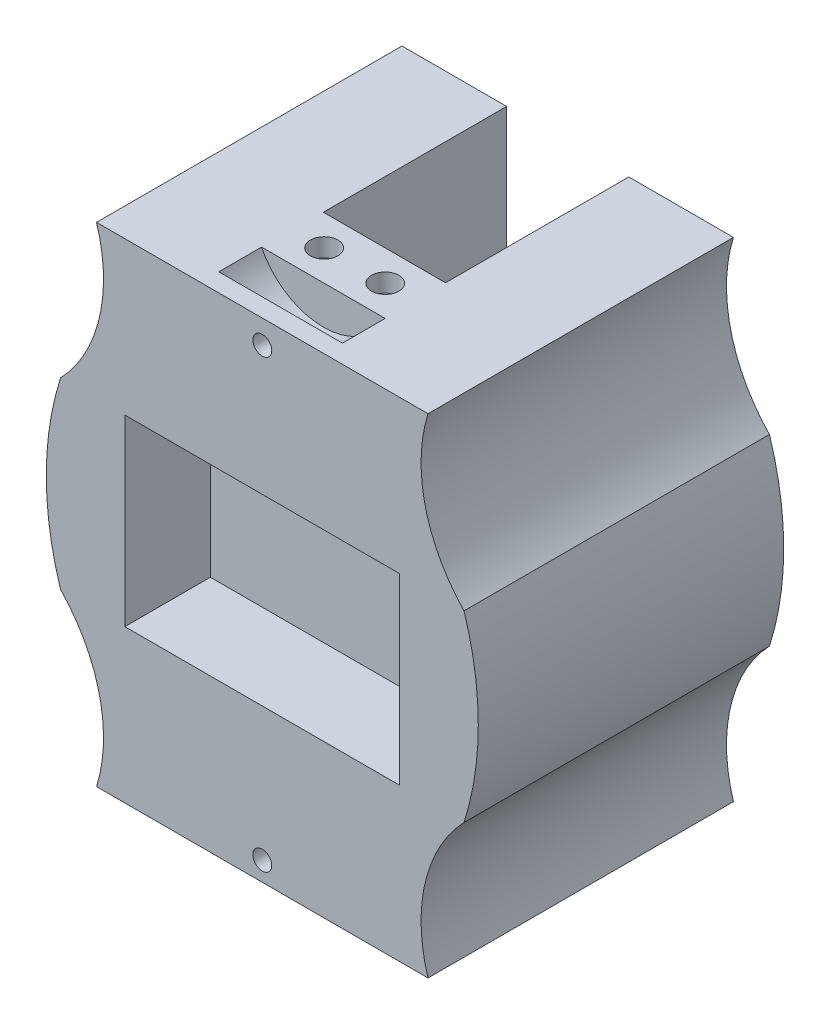
SolidWorks part; units mm, degrees
ref_plane "前视基准面" through (0, 0, 0) normal (0, 0, 1) x (1, 0, 0)
ref_plane "上视基准面" through (0, 0, 0) normal (0, 1, 0) x (1, 0, 0)
ref_plane "右视基准面" through (0, 0, 0) normal (1, 0, 0) x (0, 0, -1)
sketch "草图1" plane through (0, 0, 0) normal (0, 0, 1) x (1, 0, 0)
  line L0 (-50, -40) -> (-32.5, -40)
  line L1 (-50, 40) -> (50, 40)
  line L2 (-50, 40) -> (-50, -40)
  line L3 (-50, -40) -> (50, -40)
  line L4 (50, 40) -> (50, -40)
  line L5 (-50, 40) -> (50, -40) construction
  line L6 (-50, -40) -> (50, 40) construction
  line L7 (-32.5, -40) -> (32.5, -40)
  line L8 (-32.5, -40) -> (-32.5, 40)
  line L9 (-32.5, 40) -> (32.5, 40)
  line L10 (32.5, -40) -> (32.5, 40)
  line L11 (-32.5, -40) -> (32.5, 40) construction
  line L12 (-32.5, 40) -> (32.5, -40) construction
  line L13 (-50, 15) -> (50, 15)
  line L14 (-50, 15) -> (-50, -15)
  line L15 (-50, -15) -> (50, -15)
  line L16 (50, 15) -> (50, -15)
  line L17 (-50, 15) -> (50, -15) construction
  line L18 (-50, -15) -> (50, 15) construction
  line L19 (0, 0) -> (0, -24.7451) construction
  line L20 (0, -24.7451) -> (0, 0) construction
  line L21 (0, 0) -> (19.4056, 0) construction
  arc A0 (-50, -15) -> (-41.25, -40) centre (-58.125, -31.875) cw
  arc A1 (50, -15) -> (41.25, -40) centre (58.125, -31.875) ccw
  arc A2 (50, 15) -> (41.25, 40) centre (58.125, 31.875) cw
  arc A3 (-50, 15) -> (-41.25, 40) centre (-58.125, 31.875) ccw
  point P0 (0, 0)
  point P6 (0, 0)
  point P11 (0, 0)
  dimension "D1" = 100
  dimension "D2" = 80
  dimension "D3" = 65
  dimension "D4" = 30
  dimension "D5" = 0
extrude "凸台-拉伸1" add sketch "草图1" along normal blind 30 contours L8 L13 L10 L1 | A3 L13 L8 L1 | L13 A2 L1 L10 | L10 L15 L4 L13 | L8 L15 L10 L13 | L2 L15 L8 L13 | L15 A0 L3 L8 | L15 L8 L3 L10 | A1 L15 L10 L3
sketch "草图2" plane through (0, 0, 30) normal (0, 0, 1) x (1, 0, 0)
  line L0 (-41.25, 40) -> (41.25, 40) construction
  line L5 (41.25, 40) -> (0, 40) construction
  line L6 (-41.25, 40) -> (-56.5468, 71.4803)
  line L11 (0, 0) -> (0, 40) construction
  line L12 (10.1194, 40) -> (41.25, 40)
  line L13 (-87.5, 15) -> (-12.5, 15)
  line L14 (-41.25, 40) -> (-56.5468, 71.4803)
  line L16 (-56.5468, 71.4803) -> (-31.3626, 83.7177)
  line L19 (-87.5, 15) -> (-87.5, -15)
  line L20 (-10.1194, 40) -> (-41.25, 40)
  line L21 (56.5468, 71.4803) -> (31.3626, 83.7177)
  line L22 (41.25, 40) -> (56.5468, 71.4803)
  line L23 (-50, 15) -> (-50, -15) construction
  line L24 (-50, -15) -> (-50, 0) construction
  line L25 (-50, 0) -> (50, 0) construction
  line L26 (50, 15) -> (50, -15) construction
  line L27 (-10.1194, -40) -> (-41.25, -40)
  line L28 (-41.25, -40) -> (-56.5468, -71.4803)
  line L29 (-56.5468, -71.4803) -> (-31.3626, -83.7177)
  line L30 (56.5468, -71.4803) -> (31.3626, -83.7177)
  line L31 (41.25, -40) -> (56.5468, -71.4803)
  line L32 (10.1194, -40) -> (41.25, -40)
  line L33 (-87.5, -15) -> (-12.5, -15)
  line L34 (-12.5, 15) -> (-12.5, -15)
  line L35 (-87.5, 15) -> (-12.5, -15) construction
  line L36 (-87.5, -15) -> (-12.5, 15) construction
  line L37 (87.5, -15) -> (12.5, -15)
  line L38 (12.5, 15) -> (12.5, -15)
  line L39 (87.5, 15) -> (12.5, 15)
  line L40 (87.5, 15) -> (87.5, -15)
  arc A0 (-31.3626, 83.7177) -> (-10.1194, 40) centre (45.9871, 94.2833) ccw
  arc A1 (31.3626, 83.7177) -> (10.1194, 40) centre (-45.9871, 94.2833) cw
  arc A2 (-31.3626, -83.7177) -> (-10.1194, -40) centre (45.9871, -94.2833) cw
  arc A3 (31.3626, -83.7177) -> (10.1194, -40) centre (-45.9871, -94.2833) ccw
  line M6 (41.25, 40) -> (-41.25, 40)
  line M8 (-50, 15) -> (-50, -15)
  line M10 (-41.25, -40) -> (41.25, -40)
  line M12 (50, -15) -> (50, 15)
  dimension "D1" = 35
  dimension "D2" = 28
  dimension "D3" = 75
extrude "凸台-拉伸2" add sketch "草图2" against normal blind 10 contours L40 L39 L37 M12 | L21 A1 L22 M6 | A0 L16 L6 M6 | L19 L33 L13 M8 | L29 A2 L28 M10 | A3 L30 L31 M10
sketch "草图3" plane through (0, 0, 30) normal (0, 0, 1) x (1, 0, 0)
  line L0 (-10.1194, 40) -> (10.1194, 40)
  line L1 (-10.1194, 40) -> (10.1194, 40) construction
  line L2 (10.1194, 40) -> (30.1194, 40)
  line L3 (50, 15) -> (35, 15)
  line L4 (0, 0) -> (0, -59.6599) construction
  line L5 (0, -59.6599) -> (0, 0) construction
  line L6 (-101.1534, 0) -> (101.1534, 0) construction
  line L7 (-10.1194, 40) -> (-30.1194, 40)
  line L8 (-50, 15) -> (-35, 15)
  line L9 (10.1194, -40) -> (30.1194, -40)
  line L10 (-10.1194, -40) -> (10.1194, -40)
  line L11 (-10.1194, -40) -> (-30.1194, -40)
  arc A0 (10.1194, 40) -> (31.3626, 83.7177) centre (-45.9871, 94.2833) ccw construction
  arc A1 (30.1194, 40) -> (35, 15) centre (64.7114, 33.7768) ccw
  arc A2 (-30.1194, 40) -> (-35, 15) centre (-64.7114, 33.7768) cw
  arc A3 (30.1194, -40) -> (35, -15) centre (64.7114, -33.7768) cw
  arc A4 (-30.1194, -40) -> (-35, -15) centre (-64.7114, -33.7768) ccw
  arc A5 (-35, 15) -> (-35, -15) centre (-3.9777, 0) ccw
  arc A6 (35, 15) -> (35, -15) centre (3.9777, 0) cw
  arc A7 (-10.1194, 40) -> (10.1194, 40) centre (0, 44.9919) ccw
  arc A8 (-10.1194, -40) -> (10.1194, -40) centre (0, -44.9919) cw
  line M7 (10.1194, 40) -> (-10.1194, 40)
  arc M8 (-10.1194, 40) -> (-31.3626, 83.7177) centre (45.9871, 94.2833) cw
  line M9 (-31.3626, 83.7177) -> (-56.5468, 71.4803)
  line M10 (-56.5468, 71.4803) -> (-41.25, 40)
  arc M11 (-41.25, 40) -> (-50, 15) centre (-58.125, 31.875) cw
  line M12 (-50, 15) -> (-87.5, 15)
  line M13 (-87.5, 15) -> (-87.5, -15)
  line M14 (-87.5, -15) -> (-50, -15)
  arc M15 (-50, -15) -> (-41.25, -40) centre (-58.125, -31.875) cw
  line M16 (-41.25, -40) -> (-56.5468, -71.4803)
  line M17 (-56.5468, -71.4803) -> (-31.3626, -83.7177)
  arc M18 (-31.3626, -83.7177) -> (-10.1194, -40) centre (45.9871, -94.2833) cw
  line M19 (-10.1194, -40) -> (10.1194, -40)
  arc M20 (10.1194, -40) -> (31.3626, -83.7177) centre (-45.9871, -94.2833) cw
  line M21 (31.3626, -83.7177) -> (56.5468, -71.4803)
  line M22 (56.5468, -71.4803) -> (41.25, -40)
  arc M23 (41.25, -40) -> (50, -15) centre (58.125, -31.875) cw
  line M24 (50, -15) -> (87.5, -15)
  line M25 (87.5, -15) -> (87.5, 15)
  line M26 (87.5, 15) -> (50, 15)
  arc M27 (50, 15) -> (41.25, 40) centre (58.125, 31.875) cw
  line M28 (41.25, 40) -> (56.5468, 71.4803)
  line M29 (56.5468, 71.4803) -> (31.3626, 83.7177)
  arc M30 (31.3626, 83.7177) -> (10.1194, 40) centre (-45.9871, 94.2833) cw
  dimension "D1" = 20
  dimension "D2" = 20.2388
  dimension "D3" = 15
extrude "切除-拉伸2" cut sketch "草图3" against normal blind 10 contours A2 L7 L8 M8 M9 M10 M11 | L2 A1 L3 M27 M28 M29 M30 | L3 A6 A3 L9 M20 M21 M22 M23 M24 M25 M26 | A5 L8 L11 A4 M12 M13 M14 M15 M16 M17 M18 | A7 M7 | A8 M19
sketch "草图4" plane through (0, 0, 30) normal (0, 0, 1) x (1, 0, 0)
  line L1 (-22.5, 15) -> (22.5, 15)
  line L2 (-22.5, 15) -> (-22.5, -15)
  line L3 (-22.5, -15) -> (22.5, -15)
  line L4 (22.5, 15) -> (22.5, -15)
  line L5 (-22.5, 15) -> (22.5, -15) construction
  line L6 (-22.5, -15) -> (22.5, 15) construction
  point P0 (0, 0)
  dimension "D1" = 30
  dimension "D2" = 45
extrude "切除-拉伸3" cut sketch "草图4" against normal blind 6 contours L2 L1 L4 L3
sketch "草图5" plane through (0, 0, 30) normal (0, 0, 1) x (1, 0, 0)
  line L0 (-35, 15) -> (-22.5, 15)
  line L1 (-22.5, 15) -> (-22.5, -15) construction
  line L2 (-22.5, 15) -> (22.5, 15) construction
  line L3 (-35, -15) -> (-22.5, -15)
  line L4 (0, 0) -> (-12.8145, 0)
  line L5 (-12.8145, 0) -> (0, 0)
  line L6 (0, -22.7736) -> (0, 22.7736)
  line L7 (-27.1337, 40) -> (-30.1194, 40)
  arc A0 (-30.1194, 40) -> (-35, 15) centre (-64.7114, 33.7768) cw
  arc A1 (-27.1337, 40) -> (-33.0272, 15) centre (-51.2597, 32.4928) cw
  arc A2 (-35, 15) -> (-35, -15) centre (-3.9777, 0) ccw
  arc A3 (-33.0272, 15) -> (-33.0272, -15) centre (14.0025, 0) ccw
  arc A4 (-27.1337, -40) -> (-33.0272, -15) centre (-51.2597, -32.4928) ccw
  arc A5 (27.1337, -40) -> (33.0272, -15) centre (51.2597, -32.4928) cw
  arc A6 (33.0272, 15) -> (33.0272, -15) centre (-14.0025, 0) cw
  arc A7 (27.1337, 40) -> (33.0272, 15) centre (51.2597, 32.4928) ccw
extrude "切除-拉伸13" cut sketch "草图5" against normal blind 16
sketch "草图6" plane through (0, 0, 30) normal (0, 0, 1) x (1, 0, 0)
  line L0 (-10.1194, 40) -> (10.1194, 40)
  line L1 (-10.1194, -40) -> (10.1194, -40)
  arc A0 (-10.1194, -40) -> (10.1194, -40) centre (0, -44.9919) cw
  arc A1 (-10.1194, 40) -> (10.1194, 40) centre (0, 44.9919) ccw
extrude "凸台-拉伸3" add sketch "草图6" against normal blind 3
sketch "草图7" plane through (0, 0, 27) normal (0, 0, -1) x (-1, 0, 0)
  line L0 (0, -40) -> (0, -33.7082)
  line L1 (10.1194, -40) -> (-10.1194, -40) construction
  line L2 (0, -33.7082) -> (0, -36.8541)
  arc A0 (10.1194, -40) -> (-10.1194, -40) centre (0, -44.9919) ccw construction
  circle A1 centre (0, -36.8541) radius 1.55
  dimension "D1" = 3.1
extrude "切除-拉伸14" cut sketch "草图7" against normal blind 3 contours L0 A1 | L0 A1
sketch "草图8" plane through (0, 0, 27) normal (0, 0, -1) x (-1, 0, 0)
  line L0 (0, -36.8541) -> (0, 36.1459)
  circle A1 centre (0, 36.1459) radius 1.55
  dimension "D1" = 3.1
  dimension "D2" = 73
extrude "切除-拉伸16" cut sketch "草图8" against normal blind 6.1008
sketch "草图10" plane through (0, 0, 30) normal (0, 0, 1) x (1, 0, 0)
  line L0 (-27.1337, 40) -> (27.1337, 40)
  line L1 (27.1337, -40) -> (-27.1337, -40)
  line L2 (-155.6464, 80.8632) -> (70.8313, 55.9354)
  line L3 (70.8313, 55.9354) -> (148.6545, 0)
  line L4 (148.6545, 0) -> (148.6545, -24.3198)
  line L5 (1.824, -88.1591) -> (-119.4708, -24.3198)
  line L6 (-119.4708, -24.3198) -> (-155.6464, 80.8632)
  line L7 (1.824, -88.1591) -> (148.6545, -24.3198)
  arc A0 (27.1337, 40) -> (33.0272, 15) centre (51.2597, 32.4928) ccw
  arc A1 (33.0272, 15) -> (33.0272, -15) centre (-14.0025, 0) cw
  arc A2 (33.0272, -15) -> (27.1337, -40) centre (51.2597, -32.4928) ccw
  arc A3 (-27.1337, 40) -> (-33.0272, 15) centre (-51.2597, 32.4928) cw
  arc A4 (-33.0272, 15) -> (-33.0272, -15) centre (14.0025, 0) ccw
  arc A5 (-33.0272, -15) -> (-27.1337, -40) centre (-51.2597, -32.4928) cw
extrude "切除-拉伸17" cut sketch "草图10" against normal blind 70
sketch "草图11" plane through (0, 0, 0) normal (0, 0, -1) x (-1, 0, 0)
  line L0 (-27.1337, 40) -> (27.1337, 40)
  line L1 (-27.1337, -40) -> (27.1337, -40)
  arc A0 (27.1337, 40) -> (33.0272, 15) centre (51.2597, 32.4928) ccw
  arc A1 (33.0272, 15) -> (33.0272, -15) centre (-14.0025, 0) cw
  arc A2 (33.0272, -15) -> (27.1337, -40) centre (51.2597, -32.4928) ccw
  arc A3 (-27.1337, -40) -> (-33.0272, -15) centre (-51.2597, -32.4928) ccw
  arc A4 (-33.0272, -15) -> (-33.0272, 15) centre (14.0025, 0) cw
  arc A5 (-33.0272, 15) -> (-27.1337, 40) centre (-51.2597, 32.4928) ccw
extrude "凸台-拉伸4" add sketch "草图11" along normal blind 20
sketch "草图19" plane through (0, 40, 0) normal (0, 1, 0) x (1, 0, 0)
  line L0 (-27.1337, 20) -> (27.1337, 20) construction
  line L1 (-10, 50) -> (10, 50)
  line L2 (-10, 50) -> (-10, -10)
  line L3 (-10, -10) -> (10, -10)
  line L4 (10, 50) -> (10, -10)
  line L5 (-10, 50) -> (10, -10) construction
  line L6 (-10, -10) -> (10, 50) construction
  point P0 (0, 20)
  dimension "D1" = 20
  dimension "D2" = 60
extrude "切除-拉伸25" cut sketch "草图19" against normal blind 26.5
sketch "草图20" plane through (0, 0, -20) normal (0, 0, -1) x (-1, 0, 0)
  line L0 (-10, 13.5) -> (-10, 8.5)
  line L1 (-10, 8.5) -> (-4.875, 8.5)
  circle A0 centre (-4.875, 8.5) radius 2.25
  dimension "D3" = 4.5
  dimension "D1" = 5
  dimension "D2" = 5.125
sketch "草图21" plane through (0, 40, 0) normal (0, 1, 0) x (1, 0, 0)
  line L0 (-10, -10) -> (-10, -15)
  line L1 (-10, -15) -> (-4.875, -15)
  circle A0 centre (-4.875, -15) radius 2.25
  dimension "D3" = 4.5
  dimension "D1" = 5
  dimension "D2" = 5.125
extrude "切除-拉伸27" cut sketch "草图21" against normal blind 3
sketch "草图22" plane through (0, 40, 0) normal (0, 1, 0) x (1, 0, 0)
  line L0 (-4.875, -15) -> (5.125, -15)
  circle A0 centre (5.125, -15) radius 2.25
  dimension "D2" = 4.5
  dimension "D1" = 10
extrude "切除-拉伸28" cut sketch "草图22" against normal blind 3 contours A0
sketch "草图23" plane through (0, 0, -20) normal (0, 0, -1) x (-1, 0, 0)
  line L0 (-33.0272, 15) -> (-33.0272, -15)
  line L1 (-10, 40) -> (10, 40)
  line L2 (-10, 40) -> (-10, 13.5)
  line L3 (-10, 13.5) -> (10, 13.5)
  line L4 (10, 40) -> (10, 13.5)
  line L5 (-33.0272, -15) -> (-33.0272, 0)
  line L6 (-33.0272, 0) -> (37.6478, 0)
  line L7 (-10, -13.5) -> (10, -13.5)
  line L8 (10, -40) -> (10, -13.5)
  line L9 (-10, -40) -> (10, -40)
  line L10 (-10, -40) -> (-10, -13.5)
  line M5 (-10, 13.5) -> (-10, 40)
  line M10 (-27.1337, -40) -> (27.1337, -40)
  line M15 (10, 40) -> (10, 13.5)
  line M16 (10, 13.5) -> (-10, 13.5)
extrude "切除-拉伸29" cut sketch "草图23" against normal blind 30 contours L10 L8 L7 M10 | L1 M5 M16 M15
sketch "草图24" plane through (0, -40, 0) normal (0, -1, 0) x (1, 0, 0)
  line L0 (-10, 10) -> (-10, 15)
  line L1 (-10, 15) -> (-4.875, 15)
  line L2 (-4.875, 15) -> (5.125, 15)
  circle A0 centre (-4.875, 15) radius 2.25
  circle A1 centre (5.125, 15) radius 2.25
  dimension "D3" = 4.5
  dimension "D5" = 4.5
  dimension "D1" = 5
  dimension "D2" = 5.125
  dimension "D4" = 10
extrude "切除-拉伸30" cut sketch "草图24" against normal blind 3
sketch "草图25" plane through (0, 0, -20) normal (0, 0, -1) x (-1, 0, 0)
  circle A0 centre (-28.2212, 10.0179) radius 2
  circle A1 centre (-28.2212, -3.2986) radius 2
  dimension "D1" = 4
  dimension "D2" = 4
extrude "凸台-拉伸5" add sketch "草图25" along normal blind 6
sketch "草图26" plane through (0, 0, 24) normal (0, 0, 1) x (1, 0, 0)
  line L1 (-22.5, 15) -> (22.5, 15)
  line L2 (-22.5, 15) -> (-22.5, -15)
  line L3 (-22.5, -15) -> (22.5, -15)
  line L4 (22.5, 15) -> (22.5, -15)
extrude "切除-拉伸31" cut sketch "草图26" against normal blind 8
sketch "草图27" plane through (0, 0, -20) normal (0, 0, -1) x (-1, 0, 0)
  circle A2 centre (-28.2212, -3.2986) radius 2
  circle A3 centre (-28.2212, 10.0179) radius 2
extrude "切除-拉伸33" cut sketch "草图27" along normal blind 13 and the other way blind 13 contours A2 | A3
sketch "草图28" plane through (0, 0, -20) normal (0, 0, -1) x (-1, 0, 0)
  circle A0 centre (-28.2212, 10.0179) radius 2
